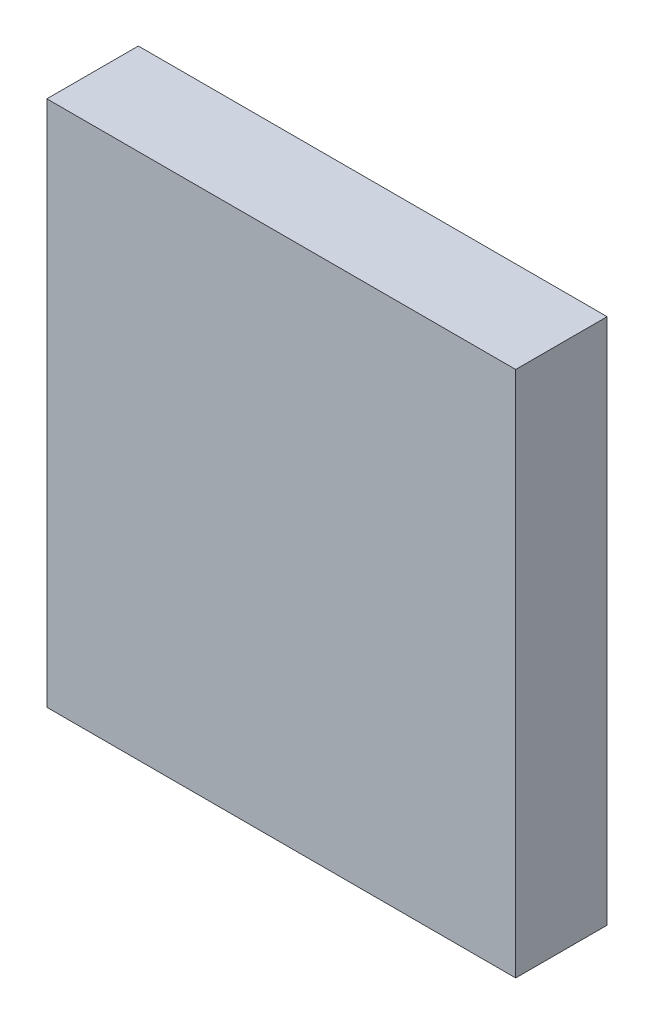
SolidWorks part; units mm, degrees
ref_plane "Ebene vorne" through (0, 0, 0) normal (0, 0, 1) x (1, 0, 0)
ref_plane "Ebene oben" through (0, 0, 0) normal (0, 1, 0) x (1, 0, 0)
ref_plane "Ebene rechts" through (0, 0, 0) normal (1, 0, 0) x (0, 0, -1)
sketch "Skizze1" plane through (0, 0, 0) normal (0, 0, 1) x (1, 0, 0)
  line L0 (-2.5635, 3.2) -> (2.5635, 3.2)
  line L1 (2.5635, 3.2) -> (2.5635, -2.5635)
  line L2 (2.5635, -2.5635) -> (-2.5635, -2.5635)
  line L3 (-2.5635, -2.5635) -> (-2.5635, 3.2)
extrude "Component_Outline" add sketch "Skizze1" along normal blind 1 separate body
sketch3d "3D-Skizze1"
  line L0 (0, 0, 0) -> (1, 0, 0)
  line L1 (0, 0, 0) -> (0, 1, 0)
  line L2 (0, 0, 0) -> (0, 0, 1)
  point P0 (0, 0, 0)
